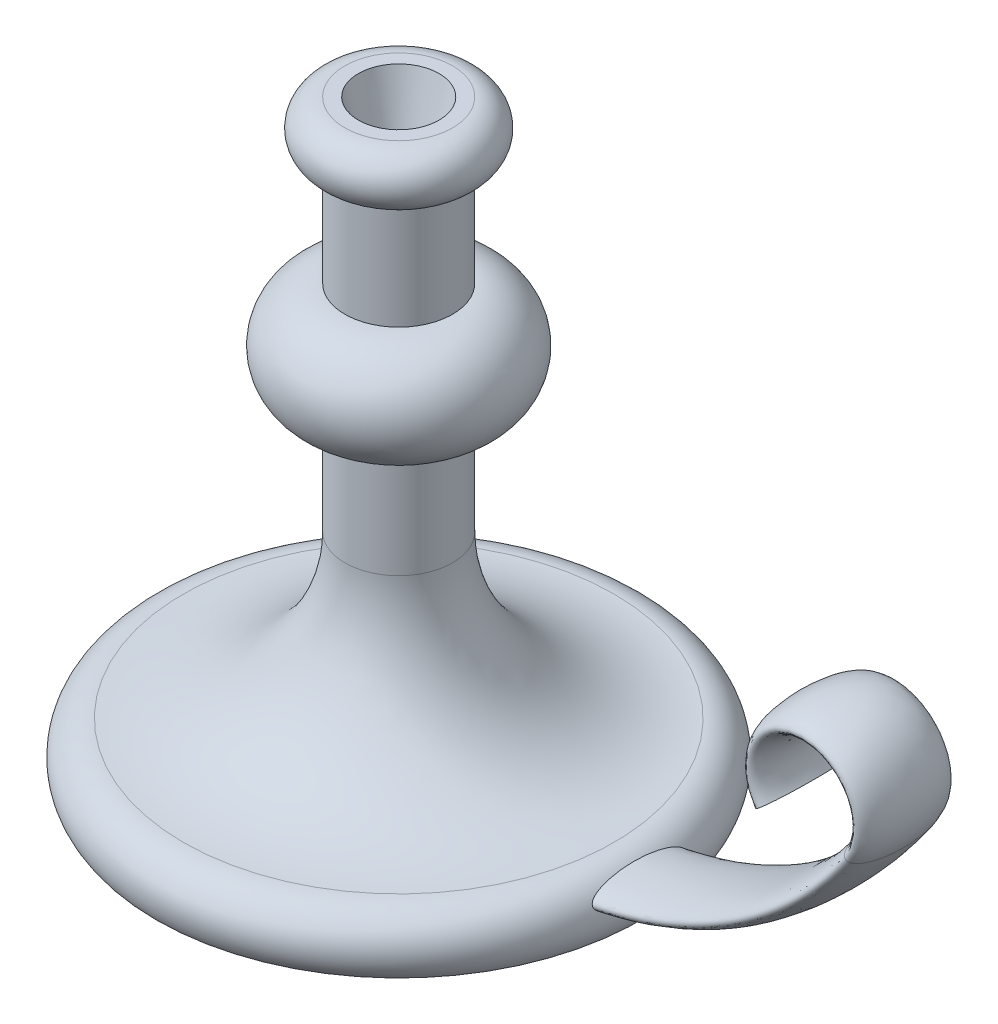
SolidWorks part; units mm, degrees
material "Copper"
ref_plane "Front Plane" through (0, 0, 0) normal (0, 0, 1) x (1, 0, 0)
ref_plane "Top Plane" through (0, 0, 0) normal (0, 1, 0) x (1, 0, 0)
ref_plane "Right Plane" through (0, 0, 0) normal (1, 0, 0) x (0, 0, -1)
sketch "Sketch1" plane through (0, 0, 0) normal (0, 0, 1) x (1, 0, 0)
  line L0 (0, 0) -> (0, 220)
  line L1 (0, 220) -> (20, 220)
  line L2 (0, 0) -> (90, 0)
  line L3 (20, 200) -> (20, 160)
  line L4 (20, 120) -> (20, 80)
  arc A0 (20, 220) -> (20, 200) centre (20, 210) cw
  arc A1 (20, 160) -> (20, 120) centre (20, 140) cw
  arc A2 (20, 80) -> (80, 20) centre (80, 80) ccw
  arc A3 (80, 20) -> (90, 0) centre (80, 7.5) cw
  dimension "D4" = 10
  dimension "D6" = 20
  dimension "D7" = 60
  dimension "D9" = 12.5
  dimension "D1" = 220
  dimension "D2" = 90
  dimension "D3" = 20
  dimension "D5" = 40
  dimension "D8" = 80
revolve "Revolve1" add sketch "Sketch1" angle 360 about L0
sketch "Path" plane through (0, 0, 0) normal (0, 0, 1) x (1, 0, 0)
  line L0 (0, 10) -> (60, 10)
  line L1 (0, 227.4356) -> (0, 175.1288) construction
  line L2 (0, 164) -> (0, 92) construction
  line L3 (-90, 0) -> (90, 0) construction
  arc A0 (60, 10) -> (183.5921, 75) centre (60, 160) ccw
  arc A1 (183.5921, 75) -> (150.6342, 75) centre (167.1131, 86.3333) ccw
  point P10 (0, 0)
  point P11 (0, 0)
  dimension "D2" = 150
  dimension "D4" = 20
  dimension "D1" = 60
  dimension "D3" = 65
  dimension "D5" = 10
sketch "Sketch3" plane through (0, 0, 0) normal (1, 0, 0) x (0, 0, -1)
  ellipse E0 centre (0, 10) end of major axis (17.5, 10) minor radius 5
  point P1 (0, 0)
  point P7 (0, 0)
  dimension "D1" = 10
  dimension "D2" = 35
sweep "Sweep1" add profiles "Sketch3" path "Path"
sketch "Sketch7" plane through (0, 220, 0) normal (0, 1, 0) x (1, 0, 0)
  circle A0 centre (0, 0) radius 15
  dimension "D1" = 30
extrude "Cut-Extrude1" cut sketch "Sketch7" against normal blind 25 draft 15
